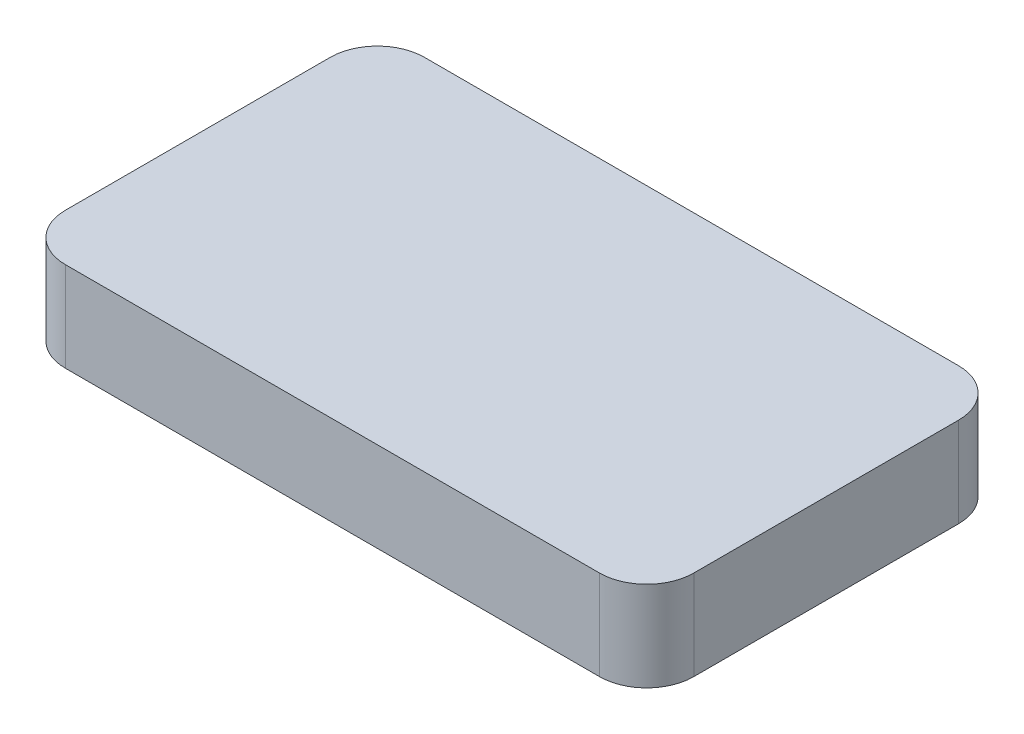
SolidWorks part; units mm, degrees
material "Low Carbon Steel"
ref_plane "Front Plane" through (0, 0, 0) normal (0, 0, 1) x (1, 0, 0)
ref_plane "Top Plane" through (0, 0, 0) normal (0, 1, 0) x (1, 0, 0)
ref_plane "Right Plane" through (0, 0, 0) normal (1, 0, 0) x (0, 0, -1)
sketch "Sketch1" plane through (0, 0, 0) normal (0, 1, 0) x (1, 0, 0)
  line L0 (-133.35, -76.2) -> (133.35, 76.2) construction
  line L1 (-133.35, 76.2) -> (133.35, 76.2)
  line L2 (-133.35, 76.2) -> (-133.35, -76.2)
  line L3 (-133.35, -76.2) -> (133.35, -76.2)
  line L4 (133.35, 76.2) -> (133.35, -76.2)
  dimension "D1" = 152.4
  dimension "D2" = 266.7
extrude "Boss-Extrude1" add sketch "Sketch1" along normal blind 38.1
fillet "Fillet1" radius 20 4 edges at (133.35, 19.05, -76.2) (-133.35, 19.05, -76.2) (-133.35, 19.05, 76.2) (133.35, 19.05, 76.2)
other "Freeze***"
